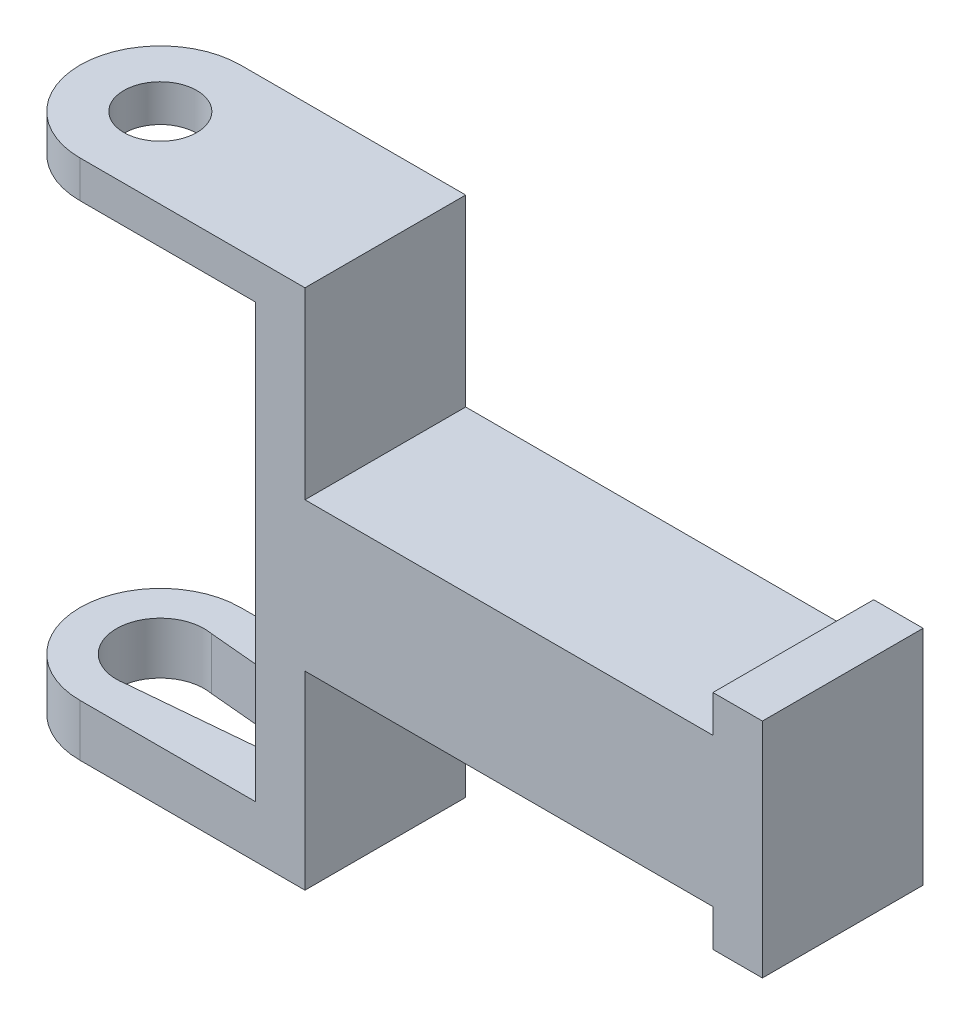
SolidWorks part; units mm, degrees
material "ABS"
ref_plane "Front Plane" through (0, 0, 0) normal (0, 0, 1) x (1, 0, 0)
ref_plane "Top Plane" through (0, 0, 0) normal (0, 1, 0) x (1, 0, 0)
ref_plane "Right Plane" through (0, 0, 0) normal (1, 0, 0) x (0, 0, -1)
sketch "Sketch1" plane through (0, 0, 0) normal (1, 0, 0) x (0, 0, -1)
  line L1 (-6.5, -89.35) -> (6.5, -89.35)
  line L2 (-6.5, -89.35) -> (-6.5, -47.15)
  line L3 (-6.5, -47.15) -> (6.5, -47.15)
  line L4 (6.5, -89.35) -> (6.5, -47.15)
extrude "Boss-Extrude1" add sketch "Sketch1" along normal mid plane 4 from offset 3
sketch "Sketch2" plane through (0, 0, 0) normal (0, 1, 0) x (1, 0, 0)
  circle A0 centre (-19.2, 0) radius 6.5
extrude "Boss-Extrude2" add sketch "Sketch2" along normal mid plane 4.2 from offset 87.25
sketch "Sketch3" plane through (0, 0, 0) normal (0, 1, 0) x (1, 0, 0)
  line L1 (-19.2, -6.5) -> (-1, -6.5)
  line L2 (-19.2, -6.5) -> (-19.2, 6.5)
  line L3 (-19.2, 6.5) -> (-1, 6.5)
  line L4 (-1, -6.5) -> (-1, 6.5)
  circle A0 centre (-19.2, 0) radius 6.5 construction
extrude "Boss-Extrude3" add sketch "Sketch3" along normal mid plane 4.2 from offset 87.25
sketch "Sketch4" plane through (0, 0, 0) normal (0, 1, 0) x (1, 0, 0)
  circle A0 centre (-19.2, 0) radius 3.55
extrude "Cut-Extrude1" cut sketch "Sketch4" against normal mid plane 4.2 from offset 87.25
sketch "Sketch5" plane through (0, 0, 0) normal (0, 1, 0) x (1, 0, 0)
  line L0 (-19.2, -3.55) -> (-6.5, -2.4033)
  line L1 (-6.5, -2.4033) -> (-6.5, 2.4033)
  line L2 (-6.5, 2.4033) -> (-19.2, 3.55)
  line L3 (-19.2, 3.55) -> (-19.2, -3.55)
  circle A0 centre (-19.2, 0) radius 3.55 construction
extrude "Cut-Extrude2" cut sketch "Sketch5" against normal mid plane 4.2 from offset 87.25
sketch "Sketch6" plane through (0, 0, 0) normal (0, 1, 0) x (1, 0, 0)
  circle A0 centre (-19.2, 0) radius 6.5
extrude "Boss-Extrude4" add sketch "Sketch6" along normal mid plane 3 from offset 48.65
sketch "Sketch7" plane through (0, 0, 0) normal (0, 1, 0) x (1, 0, 0)
  line L1 (-19.2, -6.5) -> (-1, -6.5)
  line L2 (-19.2, -6.5) -> (-19.2, 6.5)
  line L3 (-19.2, 6.5) -> (-1, 6.5)
  line L4 (-1, -6.5) -> (-1, 6.5)
  circle A0 centre (-19.2, 0) radius 6.5 construction
extrude "Boss-Extrude5" add sketch "Sketch7" along normal mid plane 3 from offset 48.65
sketch "Sketch8" plane through (0, 0, 0) normal (0, 1, 0) x (1, 0, 0)
  circle A0 centre (-19.2, 0) radius 2.95
extrude "Cut-Extrude3" cut sketch "Sketch8" against normal mid plane 3 from offset 48.65
sketch "Sketch9" plane through (0, 0, 0) normal (1, 0, 0) x (0, 0, -1)
  line L0 (-6.5, -47.15) -> (-6.5, -89.35) construction
  line L1 (-6.5, -74) -> (6.5, -74)
  line L2 (-6.5, -74) -> (-6.5, -62)
  line L3 (-6.5, -62) -> (6.5, -62)
  line L4 (6.5, -74) -> (6.5, -62)
  line L5 (6.5, -89.35) -> (6.5, -47.15) construction
extrude "Boss-Extrude6" add sketch "Sketch9" along normal mid plane 38 from offset 17
sketch "Sketch10" plane through (0, 0, 0) normal (1, 0, 0) x (0, 0, -1)
  line L0 (-6.5, -74) -> (-6.5, -89.35) construction
  line L1 (-6.5, -77) -> (6.5, -77)
  line L2 (-6.5, -77) -> (-6.5, -59)
  line L3 (-6.5, -59) -> (6.5, -59)
  line L4 (6.5, -77) -> (6.5, -59)
  line L5 (6.5, -62) -> (6.5, -47.15) construction
extrude "Boss-Extrude7" add sketch "Sketch10" along normal mid plane 4 from offset 34
